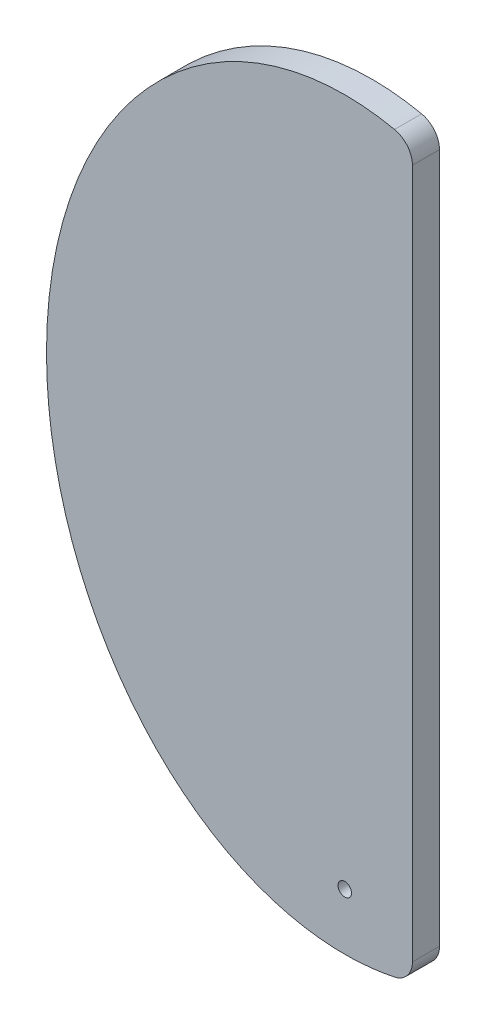
SolidWorks part; units mm, degrees
ref_plane "Front Plane" through (0, 0, 0) normal (0, 0, 1) x (1, 0, 0)
ref_plane "Top Plane" through (0, 0, 0) normal (0, 1, 0) x (1, 0, 0)
ref_plane "Right Plane" through (0, 0, 0) normal (1, 0, 0) x (0, 0, -1)
sketch "Sketch1" plane through (0, 0, 0) normal (0, 0, 1) x (1, 0, 0)
  line L0 (0, -96.0946) -> (0, 104.7292) construction
  circle A0 centre (0, -70) radius 1.5
  ellipse E0 centre (0, 0) end of major axis (0, -82.5) minor radius 66.101
  dimension "D3" = 3
  dimension "D1" = 165
  dimension "D2" = 12.5
extrude "Boss-Extrude1" add sketch "Sketch1" along normal blind 6
sketch "Sketch2" plane through (0, 0, 6) normal (0, 0, 1) x (1, 0, 0)
  line L0 (15, -139.2757) -> (15, 151.8017)
  line L1 (15, 151.8017) -> (87.8644, 144.8322)
  line L2 (87.8644, 144.8322) -> (90.2342, -139.2757)
  line L3 (90.2342, -139.2757) -> (15, -139.2757)
  line L7 (0, -139.2757) -> (0, 151.8017) construction
  dimension "D1" = 15
extrude "Cut-Extrude1" cut sketch "Sketch2" against normal blind 10
fillet "Fillet1" radius 5 2 edges at (15, -80.3477, 3) (15, 80.3477, 3)
